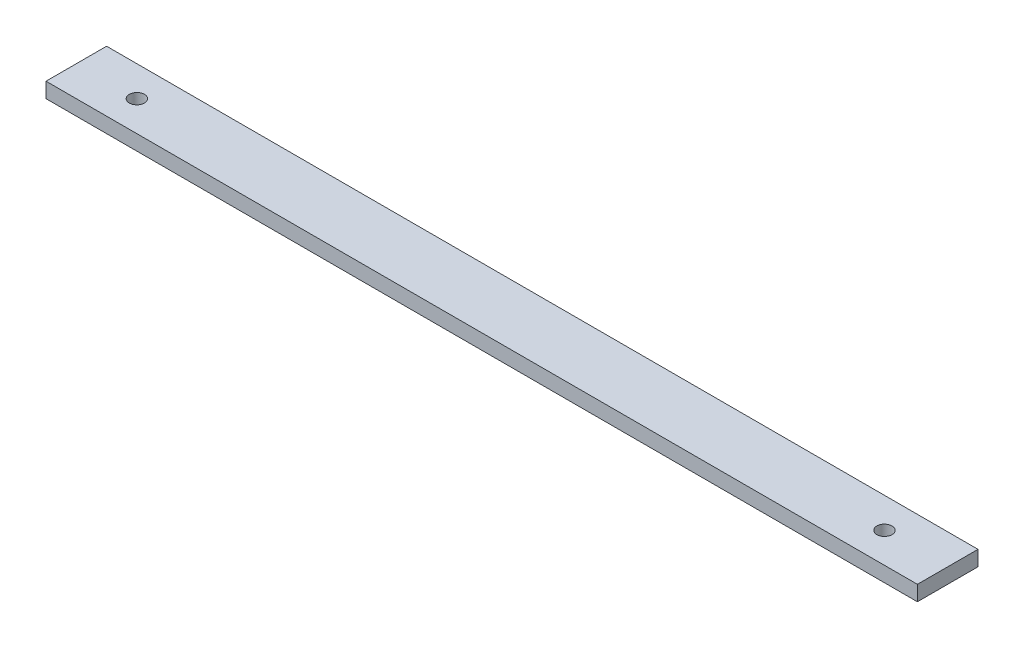
SolidWorks part; units mm, degrees
material "6061 Alloy"
ref_plane "Front Plane" through (0, 0, 0) normal (0, 0, 1) x (1, 0, 0)
ref_plane "Top Plane" through (0, 0, 0) normal (0, 1, 0) x (1, 0, 0)
ref_plane "Right Plane" through (0, 0, 0) normal (1, 0, 0) x (0, 0, -1)
sketch "Sketch1" plane through (0, 0, 0) normal (0, 1, 0) x (1, 0, 0)
  line L1 (0, 0) -> (365.252, 0)
  line L2 (0, 0) -> (0, -25.4)
  line L3 (0, -25.4) -> (365.252, -25.4)
  line L4 (365.252, 0) -> (365.252, -25.4)
  dimension "D1" = 365.252
  dimension "D2" = 25.4
extrude "Boss-Extrude1" add sketch "Sketch1" along normal blind 6.35
sketch "Sketch2" plane through (0, 0, 0) normal (0, -1, 0) x (1, 0, 0)
  line L0 (0, 0) -> (0, 25.4) construction
  line L1 (365.252, 0) -> (0, 0) construction
  circle A0 centre (25.4, 12.7) radius 3.175
  circle A1 centre (338.739, 12.7) radius 3.175
  dimension "D1" = 6.35
  dimension "D2" = 25.4
  dimension "D4" = 313.339
  dimension "D5" = 6.35
  dimension "D6" = 12.7
  dimension "D3" = 12.7
extrude "Cut-Extrude1" cut sketch "Sketch2" against normal up to next
